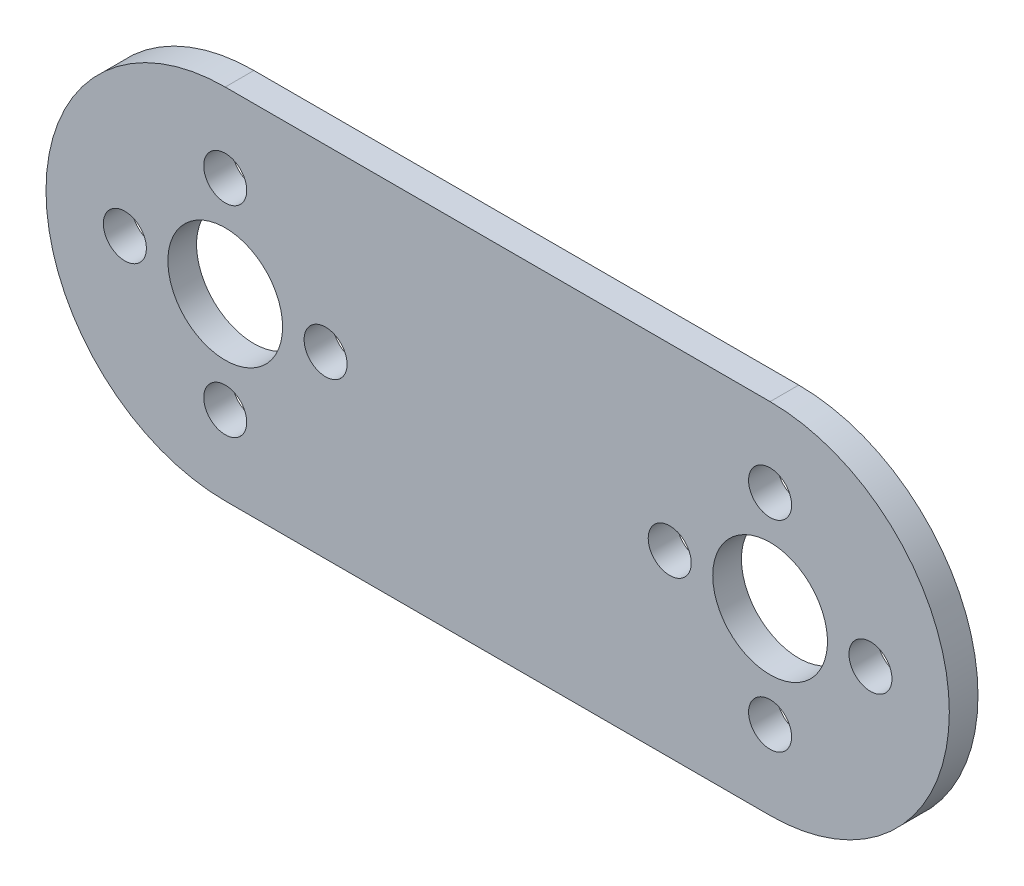
SolidWorks part; units mm, degrees
ref_plane "前视" through (0, 0, 0) normal (0, 0, 1) x (1, 0, 0)
ref_plane "上视" through (0, 0, 0) normal (0, 1, 0) x (1, 0, 0)
ref_plane "右视" through (0, 0, 0) normal (1, 0, 0) x (0, 0, -1)
sketch "草图1" plane through (0, 0, 0) normal (0, 0, 1) x (1, 0, 0)
  line L0 (0, 0) -> (38, 0) construction
  line L1 (0, 12.5) -> (38, 12.5)
  line L2 (0, -12.5) -> (38, -12.5)
  arc A0 (0, 12.5) -> (0, -12.5) centre (0, 0) ccw
  arc A1 (38, -12.5) -> (38, 12.5) centre (38, 0) ccw
  circle A2 centre (0, 0) radius 7 construction
  circle A3 centre (0, 0) radius 4
  circle A4 centre (0, 7) radius 1.5
  circle A5 centre (7, 0) radius 1.5
  circle A6 centre (0, -7) radius 1.5
  circle A7 centre (-7, 0) radius 1.5
  circle A8 centre (45, 0) radius 1.5
  circle A9 centre (38, -7) radius 1.5
  circle A10 centre (31, 0) radius 1.5
  circle A11 centre (38, 7) radius 1.5
  circle A12 centre (38, 0) radius 4
  circle A13 centre (38, 0) radius 7 construction
  point P3 (19, 0)
extrude "凸台-拉伸1" add sketch "草图1" along normal blind 2
